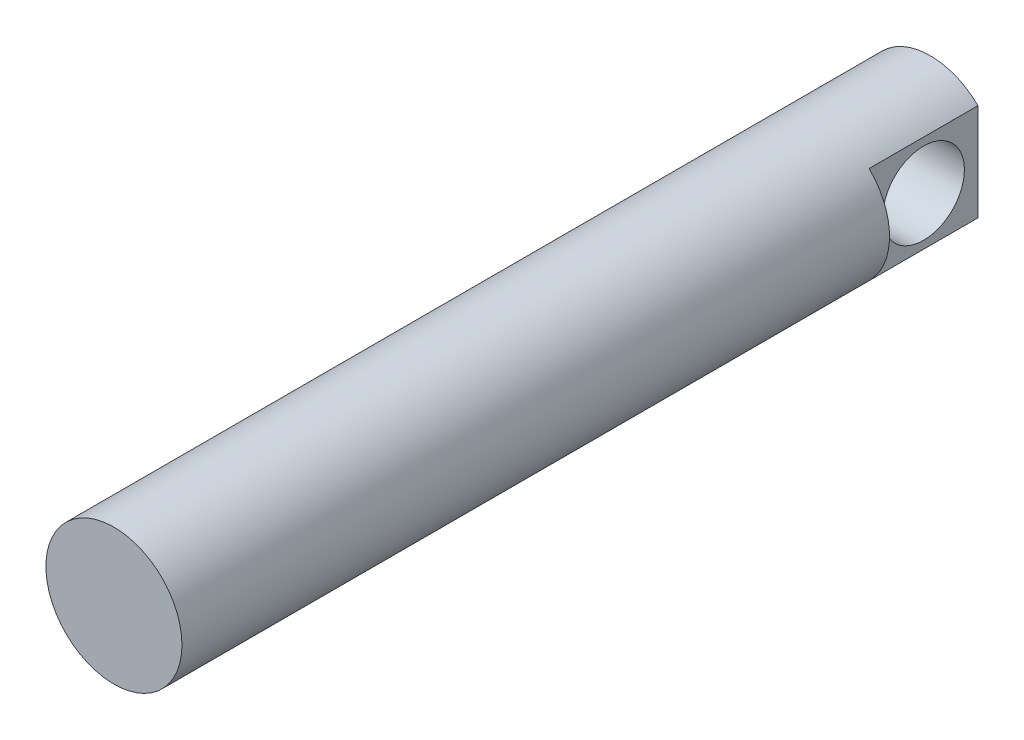
SolidWorks part; units mm, degrees
ref_plane "Front" through (0, 0, 0) normal (0, 0, 1) x (1, 0, 0)
ref_plane "Top" through (0, 0, 0) normal (0, 1, 0) x (1, 0, 0)
ref_plane "Right" through (0, 0, 0) normal (1, 0, 0) x (0, 0, -1)
sketch "Esquisse1" plane through (0, 0, 0) normal (0, 0, 1) x (1, 0, 0)
  circle A0 centre (0, 0) radius 10
  dimension "D1" = 20
extrude "Boss.-Extru.1" add sketch "Esquisse1" along normal blind 120
sketch "Esquisse2" plane through (0, 0, 0) normal (0, 0, -1) x (-1, 0, 0)
  line L0 (0, 10) -> (0, 0) construction
  line L1 (0, 0) -> (-10, 0) construction
  line L2 (-7, 7.1414) -> (-7, -7.1414)
  line L3 (7, 7.1414) -> (7, -7.1414)
  circle A0 centre (0, 0) radius 10 construction
  arc A1 (-7, 7.1414) -> (-7, -7.1414) centre (0, 0) ccw
  arc A2 (7, 7.1414) -> (7, -7.1414) centre (0, 0) cw
  point P9 (-7, 0)
  point P11 (7, 0)
  dimension "D1" = 14
extrude "Enlèv. mat.-Extru.1" cut sketch "Esquisse2" against normal blind 16
sketch "Esquisse3" plane through (7, 0, 0) normal (1, 0, 0) x (0, 0, -1)
  line L0 (0, 0) -> (-8, 0) construction
  circle A0 centre (-8, 0) radius 6
  dimension "D2" = 12
  dimension "D1" = 8
extrude "Enlèv. mat.-Extru.2" cut sketch "Esquisse3" against normal through all both and the other way through all
